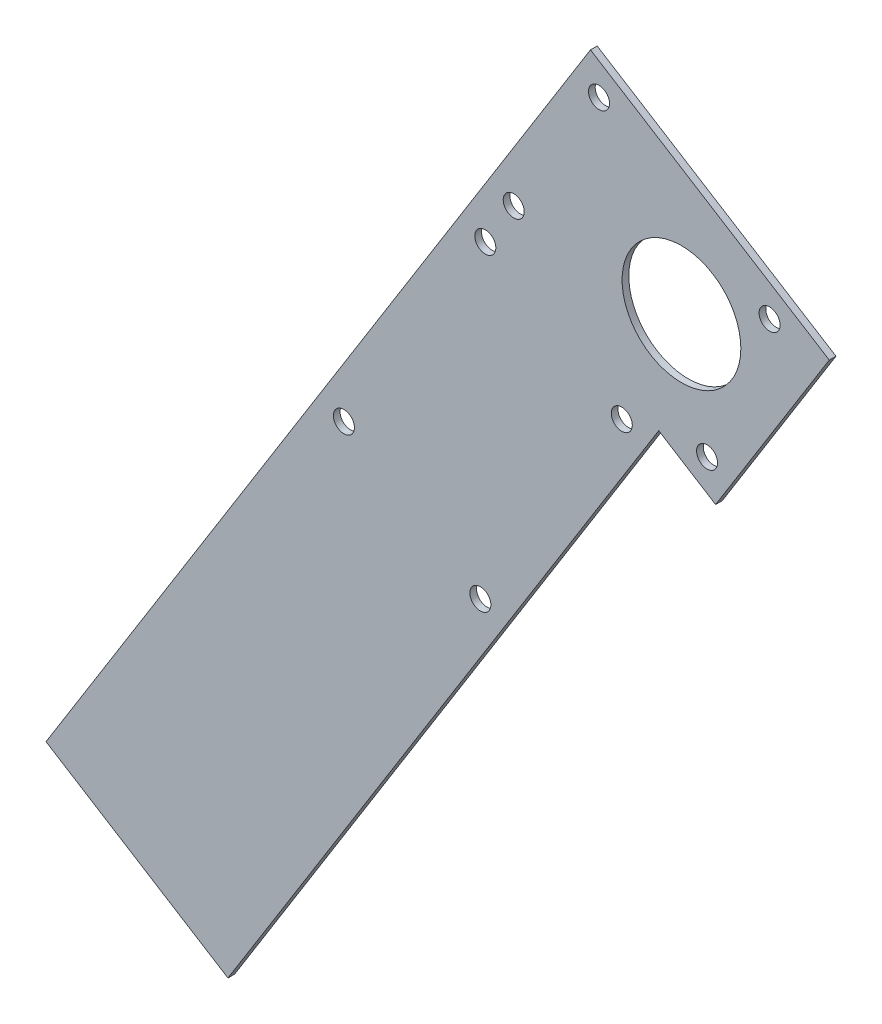
SolidWorks part; units mm, degrees
ref_plane "Front Plane" through (0, 0, 0) normal (0, 0, 1) x (1, 0, 0)
ref_plane "Top Plane" through (0, 0, 0) normal (0, 1, 0) x (1, 0, 0)
ref_plane "Right Plane" through (0, 0, 0) normal (1, 0, 0) x (0, 0, -1)
sketch "Sketch2" plane through (0, 0, 321.437) normal (0, 0, -1) x (-1, 0, 0)
  line L1 (-54.5235, -26.5823) -> (-27.6036, -69.6631)
  line L2 (-27.6036, -69.6631) -> (-14.1408, -61.2506)
  line L3 (-14.1408, -61.2506) -> (87.8513, -224.4722)
  line L4 (-14.1408, -61.2506) -> (154.1085, -330.5059) construction
  line L5 (87.8513, -224.4722) -> (130.9322, -197.5523)
  line L6 (28.94, -34.3308) -> (197.1894, -303.586) construction
  line L7 (130.9322, -197.5523) -> (2.0201, 8.7501)
  line L8 (112.4148, 77.7323) -> (-54.5235, -26.5823) construction
  line L9 (2.0201, 8.7501) -> (-54.5235, -26.5823)
extrude "Boss-Extrude1" add sketch "Sketch2" along normal blind 1.5875
hole_wizard "#10 Clearance Hole1" positions "Sketch3" profile "Sketch4" hole size "#10" standard "ANSI Inch" end condition through all
sketch "Sketch3" plane through (0, 0, 319.8495) normal (0, 0, -1) x (-1, 0, 0)
  point P0 (-5.3907, -63.2708)
  point P3 (-25.5835, -60.913)
  point P6 (-40.3883, -25.2374)
  point P9 (0, 0)
  point P12 (20.1899, -32.3106)
  point P15 (26.9199, -43.0808)
  point P18 (60.4039, -96.6664)
  point P21 (28.0932, -116.8563)
sketch "Sketch4" plane through (5.3907, -63.2708, 319.8495) normal (1, 0, 0) x (0, 1, 0)
  line L0 (0, 0) -> (0, 1.5875)
  line L1 (0, 1.5875) -> (2.4892, 1.5875)
  line L2 (2.4892, 1.5875) -> (2.4892, 0)
  line L5 (2.4892, 0) -> (0, 0)
  line L11 (0, -6.35) -> (0, 107.95) construction
  dimension "Thru Hole Dia." = 4.9784
  dimension "Thru Hole Depth" = 1.5875
sketch "Sketch5" plane through (0, 0, 321.437) normal (0, 0, 1) x (1, 0, 0)
  circle A0 centre (19.5231, -34.6627) radius 14.0572
extrude "Cut-Extrude1" cut sketch "Sketch5" against normal blind 2.54
